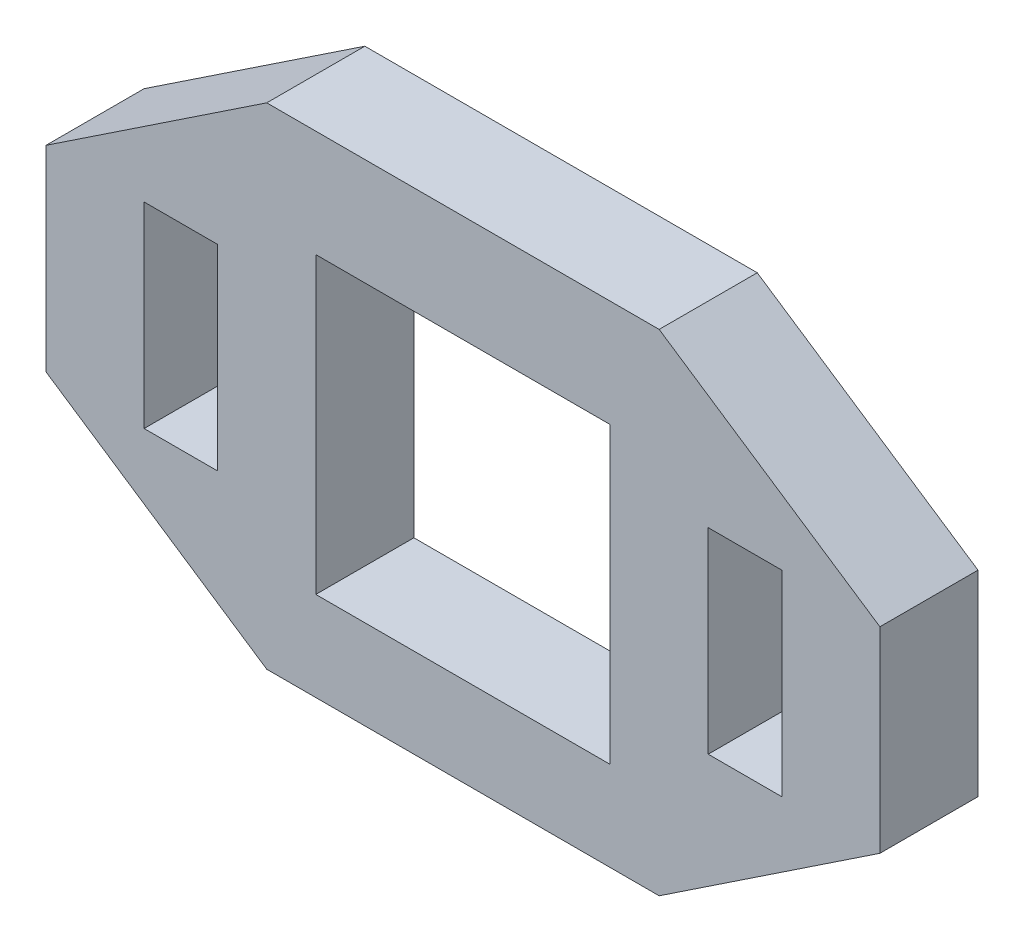
SolidWorks part; units mm, degrees
ref_plane "Front Plane" through (0, 0, 0) normal (0, 0, 1) x (1, 0, 0)
ref_plane "Top Plane" through (0, 0, 0) normal (0, 1, 0) x (1, 0, 0)
ref_plane "Right Plane" through (0, 0, 0) normal (1, 0, 0) x (0, 0, -1)
sketch "Sketch1" plane through (0, 0, 0) normal (0, 0, 1) x (1, 0, 0)
  line L0 (0, 0) -> (0, 50.8)
  line L1 (0, 50.8) -> (57.15, 88.9)
  line L2 (57.15, 88.9) -> (158.75, 88.9)
  line L3 (158.75, 88.9) -> (215.9, 50.8)
  line L4 (215.9, 50.8) -> (215.9, 0)
  line L5 (215.9, 0) -> (158.75, -38.1)
  line L6 (158.75, -38.1) -> (57.15, -38.1)
  line L7 (57.15, -38.1) -> (0, 0)
  line L9 (25.4, 0) -> (44.45, 0)
  line L10 (25.4, 0) -> (25.4, 50.8)
  line L11 (25.4, 50.8) -> (44.45, 50.8)
  line L12 (44.45, 0) -> (44.45, 50.8)
  line L13 (69.85, 61.2244) -> (146.05, 61.2244)
  line L14 (69.85, 61.2244) -> (69.85, -14.9756)
  line L15 (69.85, -14.9756) -> (146.05, -14.9756)
  line L16 (146.05, 61.2244) -> (146.05, -14.9756)
  line L17 (190.5, 50.8) -> (171.45, 50.8)
  line L18 (190.5, 50.8) -> (190.5, 0)
  line L19 (190.5, 0) -> (171.45, 0)
  line L20 (171.45, 50.8) -> (171.45, 0)
  dimension "D1" = 50.8
  dimension "D2" = 57.15
  dimension "D3" = 101.6
  dimension "D4" = 57.15
  dimension "D5" = 57.15
  dimension "D6" = 57.15
  dimension "D7" = 215.9
  dimension "D8" = 38.1
  dimension "D9" = 38.1
  dimension "D10" = 50.8
  dimension "D11" = 25.4
  dimension "D12" = 19.05
  dimension "D13" = 50.8
  dimension "D14" = 25.4
  dimension "D15" = 19.05
  dimension "D16" = 76.2
  dimension "D17" = 76.2
  dimension "D18" = 25.4
extrude "Boss-Extrude1" add sketch "Sketch1" along normal blind 25.4
